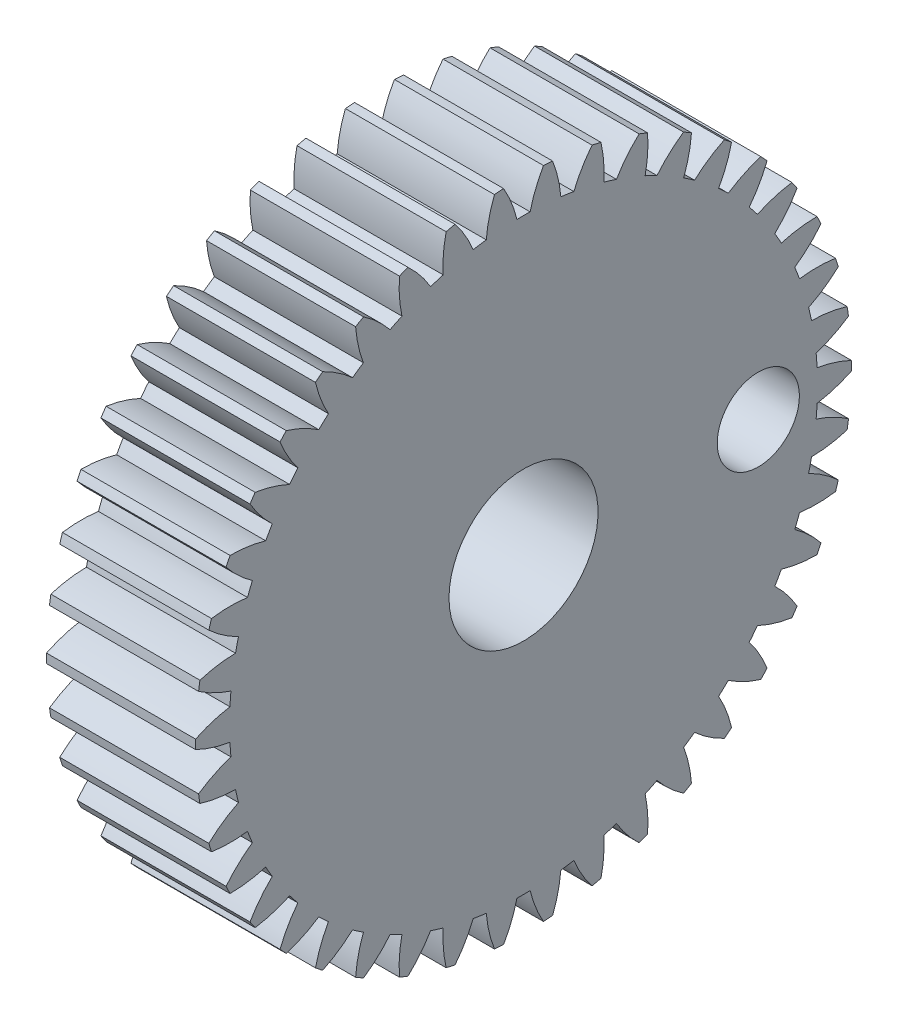
SolidWorks part; units mm, degrees
ref_plane "Plane1" through (0, 0, 0) normal (0, 0, 1) x (1, 0, 0)
ref_plane "Plane2" through (0, 0, 0) normal (0, 1, 0) x (1, 0, 0)
ref_plane "Plane3" through (0, 0, 0) normal (1, 0, 0) x (0, 0, -1)
sketch "HoldingSke" plane through (0, 0, 0) normal (0, 1, 0) x (1, 0, 0)
  line L0 (0, 0) -> (755.0351, -679.8367)
  line L1 (-15, 0) -> (100, 0) construction
  line L2 (0, 0) -> (-2.1039, 2.3779)
  line L3 (0, 0) -> (-11.863, 4.5341)
  line L4 (0, 0) -> (6.4178, 5.7786)
  line L5 (0, 0) -> (-47.5972, -17.7524)
  line L6 (0, 0) -> (-5.2639, -3.5516)
  line L7 (-2.1039, 2.3779) -> (8.8308, 51.9871)
  line L8 (-76.2, 54.61) -> (-69.596, 54.61)
  line L9 (-71.009, 38.7566) -> (-53.1078, 45.2721)
  line L10 (-76.2, 71.12) -> (104.1128, 71.12)
  line L11 (0, 0) -> (-6.35, 0)
  line L12 (-76.2, 101.6) -> (-76.1746, 101.6)
  line L13 (24.9733, 27.94) -> (52.9518, 28.4284)
  line L14 (24.9733, 27.94) -> (25.0241, 27.9398)
  line L15 (24.9733, 27.94) -> (100.4021, 29.52)
  circle A0 centre (0, 0) radius 3.175
  circle A1 centre (0, 0) radius 12.5222
  circle A2 centre (0, 0) radius 38.1
  circle A3 centre (0, 0) radius 3.175
  dimension "MHD" = 25.0444
  dimension "Hub_dia" = 76.2
  dimension "Bore" = 6.35
  dimension "MBD" = 6.35
  dimension "Num_teeth" = 42
  dimension "Pitch" = 1016
  dimension "Overall_len" = 50.8
  dimension "Show_teeth" = 42
  dimension "Thickness" = 6.35
  dimension "OAL" = 50.8001
  dimension "T_dim" = 6.604
  dimension "Ap" = 20
  dimension "H" = 19.05
  dimension "Pitch_radius" = 180.3128
  dimension "Width" = 6.35
  dimension "Backlash" = 0.0254
  dimension "Addendum_fac" = 1
  dimension "Dedendum_fac" = 1.2
  dimension "Clearance_fac" = 0.2
  dimension "Dedendum_add" = 0.0508
sketch "BasProSke" plane through (0, 0, 0) normal (0, 1, 0) x (1, 0, 0)
  line L0 (-10, 0) -> (60, 0) construction
  line L1 (0, 0) -> (0, 13.97)
  line L2 (0, 0) -> (6.35, 0)
  line L3 (6.35, 0) -> (6.35, 13.97)
  line L4 (6.35, 13.97) -> (0, 13.97)
  dimension "Thickness" = 6.35
  dimension "Diameter" = 27.94
revolve "Base-Revolve" add sketch "BasProSke" angle 360 about L0
sketch "TooCutSke" plane through (0, 0, 0) normal (1, 0, 0) x (0, 0, -1)
  line L1 (0, 0) -> (0, 107) construction
  line L2 (0, 0) -> (-0.5431, 13.3239) construction
  line L3 (0, 0) -> (-1.9919, 26.58) construction
  line L4 (-0.5431, 13.3239) -> (-0.9959, 13.29) construction
  arc A0 (0.2809, 12.519) -> (-0.2809, 12.519) centre (0, 0) ccw
  arc A1 (0.864, 13.9687) -> (-0.864, 13.9687) centre (0, 0) ccw
  circle A2 centre (0, 0) radius 13.335 construction
  circle A3 centre (0, 0) radius 12.5308 construction
  arc A4 (-0.2809, 12.519) -> (-0.864, 13.9687) centre (-5.4678, 11.2749) ccw
  arc A5 (0.864, 13.9687) -> (0.2809, 12.519) centre (5.4678, 11.2749) ccw
  dimension "Root_dia" = 25.0444
  dimension "Overcut_dia" = 27.9908
  dimension "Pitch_dia" = 26.67
  dimension "Base_dia" = 25.0616
  dimension "Flank_rad" = 5.334
  dimension "Half_ang" = 4.286
  dimension "Half_CT" = 0.4542
extrude "ToothCut" cut sketch "TooCutSke" along normal through all
fillet "Breaks" [suppressed] radius 0.0127
fillet "RootFillets" [suppressed] radius 0.1778
pattern_circular "TeethCuts" count 42 every 8.571 about axis through (-10, 0, 0) along (1, 0, 0) of "ToothCut", "RootFillets", "Breaks"
sketch "HubNeaOneSke" plane through (0, 0, 0) normal (-1, 0, 0) x (0, 0, 1)
  circle A0 centre (0, 0) radius 12.5222
  dimension "Diameter" = 25.0444
extrude "HubNearOne" [suppressed] add sketch "HubNeaOneSke" along normal blind 44.4501
sketch "HubNeaBotSke" plane through (0, 0, 0) normal (-1, 0, 0) x (0, 0, 1)
  circle A0 centre (0, 0) radius 12.5222
  dimension "Diameter" = 25.0444
extrude "HubNearBoth" [suppressed] add sketch "HubNeaBotSke" along normal blind 22.225
ref_plane "FarPln" through (6.35, 0, 0) normal (1, 0, 0) x (0, 0, -1)
sketch "HubFarSke" plane through (6.35, 0, 0) normal (1, 0, 0) x (0, 0, -1)
  circle A0 centre (0, 0) radius 12.5222
  dimension "Diameter" = 25.0444
extrude "HubFar" [suppressed] add sketch "HubFarSke" along normal blind 22.225
sketch "BorSke" plane through (0, 0, 0) normal (1, 0, 0) x (0, 0, -1)
  circle A0 centre (0, 0) radius 3.175
  dimension "Diameter" = 6.35
extrude "Bore" cut sketch "BorSke" along normal mid plane 101.6001
sketch "KeySke" plane through (0, 0, 0) normal (1, 0, 0) x (0, 0, -1)
  line L0 (-0.127, 0) -> (-0.127, 3.429)
  line L1 (-0.127, 3.429) -> (0.127, 3.429)
  line L2 (0.127, 3.429) -> (0.127, 0)
  line L3 (0, 0) -> (0, 34) construction
  line L4 (-0.127, 0) -> (0.127, 0)
  dimension "Offset" = 3.429
  dimension "Width" = 0.254
extrude "Keyway" [suppressed] cut sketch "KeySke" along normal mid plane 101.6001
pattern_circular "Keyway2" [suppressed] count 2 every 90 about axis through (-10, 0, 0) along (1, 0, 0)
sketch "Sketch1" plane through (6.35, 0, 0) normal (1, 0, 0) x (0, 0, -1)
  line L0 (0, 0) -> (13.97, 0) construction
  circle A0 centre (10, 0) radius 1.75
  circle A1 centre (0, 0) radius 3.175 construction
  circle A2 centre (0, 0) radius 3.175
  arc A3 (13.9686, -0.1947) -> (13.9686, 0.1947) centre (0, 0) ccw construction
  dimension "D2" = 3.5
  dimension "D1" = 10
extrude "Cut-Extrude1" cut sketch "Sketch1" against normal through all
equation "' \"Pitch@HoldingSke\" = 4"
equation "' \"Num_teeth@HoldingSke\" = 12"
equation "' \"Ap@HoldingSke\" =  20"
equation "' \"Ap@HoldingSke\" = 20"
equation "' \"Width@HoldingSke\" = 0.5"
equation "' \"Hub_dia@HoldingSke\"= 1"
equation "' \"Hub_dia@HoldingSke\" = 1"
equation "' \"Overall_len@HoldingSke\" = 1.0"
equation "' \"Bore@HoldingSke\" = 0.75"
equation "' \"T_dim@HoldingSke\" = 0.85"
equation "' \"Width@KeySke\" = 0.25"
equation "' \"Show_teeth@HoldingSke\" = 13"
equation "' \"Backlash@HoldingSke\" = 0.009"
equation "' \"Addendum_fac@HoldingSke\" = 1.0"
equation "' \"Dedendum_fac@HoldingSke\" = 1.25"
equation "' \"Dedendum_add@HoldingSke\" = 0.00005"
equation "' \"Clearance_fac@HoldingSke\" = 0.25"
equation "' \"Pitch@HoldingSke\" = 0.5"
equation "' \"Num_teeth@HoldingSke\" = 23"
equation "' \"Show_teeth@HoldingSke\" = 23"
equation "' \"Backlash@HoldingSke\" = 0.0375"
equation "\"Overcut_dia@TooCutSke\" = (\"Num_teeth@HoldingSke\" + 2 * \"Addendum_fac@HoldingSke\") / \"Pitch@HoldingSke\" + 0.002"
equation "\"Pitch_dia@TooCutSke\" = \"Num_teeth@HoldingSke\" / \"Pitch@HoldingSke\""
equation "\"Base_dia@TooCutSke\" = \"Num_teeth@HoldingSke\" / \"Pitch@HoldingSke\" * cos((\"Ap@HoldingSke\"  * 3.14159265 / 180))"
equation "\"Root_dia@TooCutSke\" = (\"Num_teeth@HoldingSke\" + 2) / \"Pitch@HoldingSke\" - 2 * (\"Addendum_fac@HoldingSke\" + \"Dedendum_fac@HoldingSke\") / \"Pitch@HoldingSke\" - \"Dedendum_add@HoldingSke\" * 2"
equation "\"Half_ang@TooCutSke\" = 180 / \"Num_teeth@HoldingSke\""
equation "\"Half_CT@TooCutSke\" = \"Num_teeth@HoldingSke\" / \"Pitch@HoldingSke\" * sin((3.14159265 / 2 / \"Num_teeth@HoldingSke\")) / 2 - 7 * \"Backlash@HoldingSke\" / 4"
equation "\"Flank_rad@TooCutSke\" = \"Num_teeth@HoldingSke\" / \"Pitch@HoldingSke\" / 5"
equation "\"Radius@RootFillets\" = \"Clearance_fac@HoldingSke\" / \"Pitch@HoldingSke\" + \"Dedendum_add@HoldingSke\""
equation "\"Break_rad@Breaks\" = 0.02 / \"Pitch@HoldingSke\""
equation "\"Thickness@HoldingSke\" = \"Width@HoldingSke\""
equation "\"OAL@HoldingSke\" = \"Thickness@HoldingSke\""
equation "\"MHD@HoldingSke\" = (\"Num_teeth@HoldingSke\" + 2) / \"Pitch@HoldingSke\" - 2 * (\"Addendum_fac@HoldingSke\" + \"Dedendum_fac@HoldingSke\")  / \"Pitch@HoldingSke\" - \"Dedendum_add@HoldingSke\" * 2"
equation "\"MBD@HoldingSke\" = (\"Num_teeth@HoldingSke\" + 2) / \"Pitch@HoldingSke\" - 2 * (\"Addendum_fac@HoldingSke\" + \"Dedendum_fac@HoldingSke\")  / \"Pitch@HoldingSke\" - \"Dedendum_add@HoldingSke\" * 2 - 0.002"
equation "\"MHD@HoldingSke\" = ((sgn( \"MHD@HoldingSke\" - \"Hub_dia@HoldingSke\" )-1)*( \"MHD@HoldingSke\" - \"Hub_dia@HoldingSke\" ))/-2+ \"Hub_dia@HoldingSke\""
equation "\"MBD@HoldingSke\" = ((sgn( \"MBD@HoldingSke\" - \"Bore@HoldingSke\" )-1)*( \"MBD@HoldingSke\" - \"Bore@HoldingSke\" ))/-2+ \"Bore@HoldingSke\""
equation "\"OAL@HoldingSke\" = ((sgn( \"OAL@HoldingSke\" - \"Overall_len@HoldingSke\" )+1)*( \"OAL@HoldingSke\" - \"Overall_len@HoldingSke\" ))/2 + \"Overall_len@HoldingSke\" + 0.000002"
equation "\"Num_teeth@TeethCuts\" = int( \"Show_teeth@HoldingSke\" ) + 1"
equation "\"Num_teeth@TeethCuts\" = ((sgn( \"Num_teeth@TeethCuts\" - \"Num_teeth@HoldingSke\" )-1)*( \"Num_teeth@TeethCuts\" - \"Num_teeth@HoldingSke\" ))/-2+ \"Num_teeth@HoldingSke\""
equation "\"Num_teeth@TeethCuts\" = ((sgn( \"Num_teeth@TeethCuts\" - 2.0)+1)*( \"Num_teeth@TeethCuts\" - 2.0))/2 +2.0"
equation "\"Angle@TeethCuts\" = 360.0 / \"Num_teeth@HoldingSke\""
equation "\"Diameter@BasProSke\" = (\"Num_teeth@HoldingSke\" + 2 * \"Addendum_fac@HoldingSke\") / \"Pitch@HoldingSke\""
equation "\"Thickness@BasProSke\"  = \"Thickness@HoldingSke\""
equation "' \"Fillet_rad@BasProSke\" =  \"Thickness@HoldingSke\" * 0.05"
equation "' \"Fillet_rad@BasProSke\" = \"Thickness@HoldingSke\" * 0.05"
equation "\"MHD@HoldingSke\" = ((sgn( \"MHD@HoldingSke\" - \"Root_dia@TooCutSke\" )-1)*( \"MHD@HoldingSke\" - \"Root_dia@TooCutSke\" ))/-2+ \"Root_dia@TooCutSke\""
equation "\"Diameter@HubNeaOneSke\" = \"MHD@HoldingSke\""
equation "\"Length@HubNearOne\" = \"OAL@HoldingSke\" - \"Thickness@BasProSke\""
equation "\"Diameter@HubNeaBotSke\" = \"MHD@HoldingSke\""
equation "\"Length@HubNearBoth\" = ( \"OAL@HoldingSke\" - \"Thickness@BasProSke\" ) / 2.0"
equation "\"Thickness@FarPln\" = \"Thickness@BasProSke\""
equation "\"Diameter@HubFarSke\" = \"MHD@HoldingSke\""
equation "\"Length@HubFar\" = ( \"OAL@HoldingSke\" - \"Thickness@BasProSke\" ) / 2.0"
equation "\"Diameter@BorSke\" = \"MBD@HoldingSke\""
equation "\"D1@Bore\" = \"OAL@HoldingSke\" * 2.0"
equation "\"D1@Keyway\" = \"OAL@HoldingSke\" * 2.0"
equation "\"Offset@KeySke\" = \"T_dim@HoldingSke\" - \"MBD@HoldingSke\" / 2.0"
